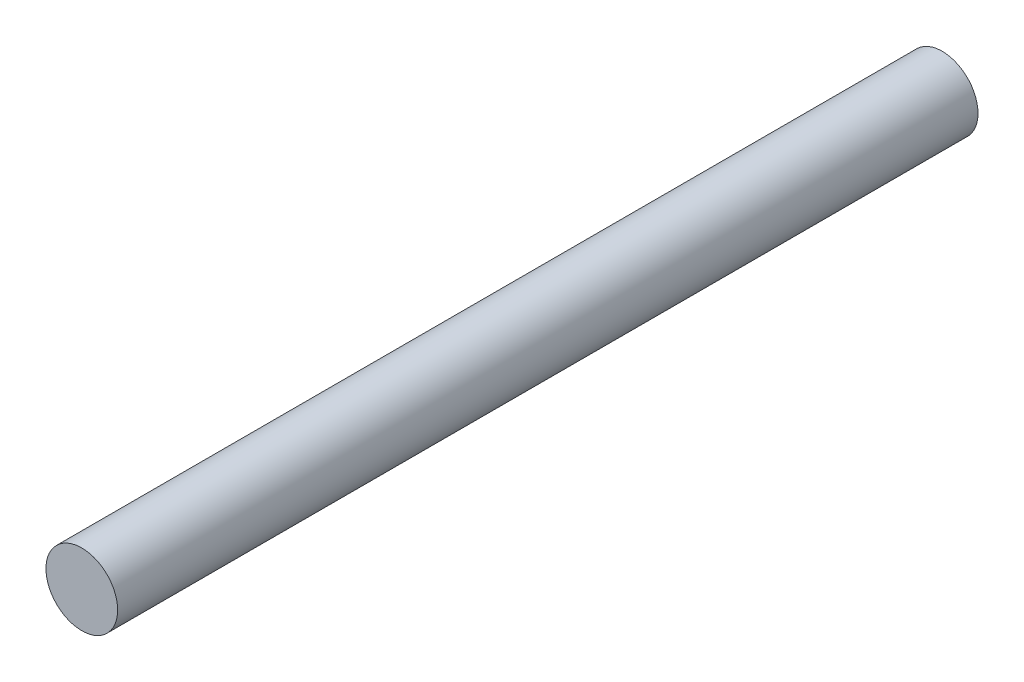
SolidWorks part; units mm, degrees
material "201 Acero inoxidable recocido (SS)"
ref_plane "Alzado" through (0, 0, 0) normal (0, 0, 1) x (1, 0, 0)
ref_plane "Planta" through (0, 0, 0) normal (0, 1, 0) x (1, 0, 0)
ref_plane "Vista lateral" through (0, 0, 0) normal (1, 0, 0) x (0, 0, -1)
sketch "Croquis1" plane through (0, 0, 0) normal (0, 0, 1) x (1, 0, 0)
  circle A0 centre (0, 0) radius 10
  dimension "D1" = 20
extrude "Saliente-Extruir1" add sketch "Croquis1" along normal blind 240
